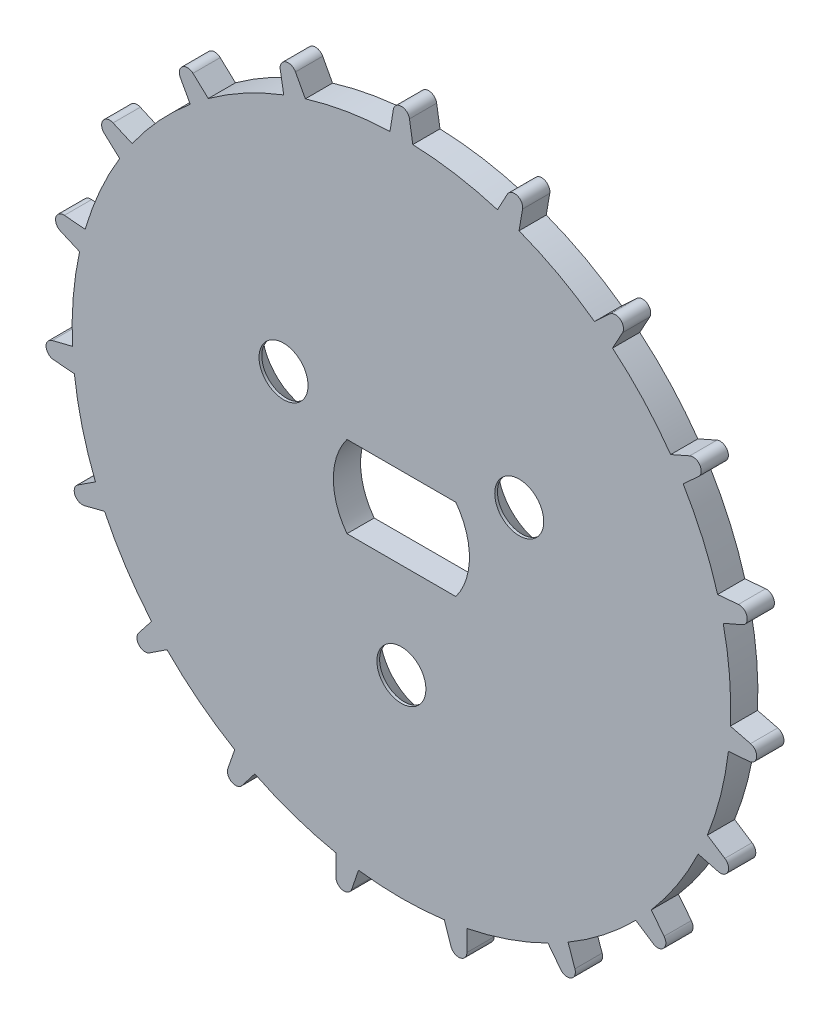
SolidWorks part; units mm, degrees
material "Нержавеющая сталь (ферритная)"
ref_plane "Спереди" through (0, 0, 0) normal (0, 0, 1) x (1, 0, 0)
ref_plane "Сверху" through (0, 0, 0) normal (0, 1, 0) x (1, 0, 0)
ref_plane "Справа" through (0, 0, 0) normal (1, 0, 0) x (0, 0, -1)
sketch "Эскиз7" plane through (0, 0, 0) normal (0, 0, 1) x (1, 0, 0)
  circle A0 centre (0, 0) radius 13.1 construction
  dimension "D1" = 26.2
sketch "Model" plane through (0, 0, 0) normal (0, 0, 1) x (1, 0, 0)
  circle A133 centre (0, 0) radius 12.1
  dimension "D1" = 24.2
extrude "База" add sketch "Model" against normal mid plane 1
sketch "Эскиз3" plane through (0, 0, 0.5) normal (0, 0, 1) x (1, 0, 0)
  line L0 (2, -1.5) -> (-2, -1.5)
  line L1 (-2, 1.5) -> (2, 1.5)
  arc A0 (-2, 1.5) -> (-2, -1.5) centre (0, 0) ccw
  arc A1 (2, -1.5) -> (2, 1.5) centre (0, 0) ccw
  point P5 (0, -1.5)
  point P6 (-2.5, 0)
  point P7 (2.5, 0)
  point P8 (0, 1.5)
  dimension "D2" = 2.5
  dimension "D1" = 4
extrude "Вырез-Вытянуть1" cut sketch "Эскиз3" along direction (0, 0, 1) on the side against the normal through all
sketch "Эскиз4" plane through (0, 0, 0.5) normal (0, 0, 1) x (1, 0, 0)
  line L0 (-0.5, 11.6) -> (0.5, 11.6)
  line L1 (-0.5, 11.6) -> (-0.2961, 12.8484)
  line L2 (0.2961, 12.8484) -> (0.5, 11.6)
  arc A5 (-0.2961, 12.8484) -> (0.2961, 12.8484) centre (0, 12.8) cw
  circle A9 centre (0, 0) radius 13.1 construction
  point P9 (0, 14.6609)
  point P15 (0, 11.6)
  dimension "D2" = 1.2
  dimension "D4" = 0.3
  dimension "D1" = 1
extrude "Зуб" add sketch "Эскиз4" against normal up to surface (1 mm away) up to face at (0, 0, -0.5)
pattern_circular "Круговой массив" count 19 over 360 about axis through (0, 0, 0) along (0, 0, 1) of "Зуб"
hole_wizard "Крепление шестерни M1.6" positions "Эскиз5" profile "Эскиз6" countersink size "M1.6" standard "DIN" end condition through all
sketch "Эскиз5" plane through (0, 0, -0.5) normal (0, 0, 1) x (1, 0, 0)
  circle A0 centre (0, 0) radius 5 construction
  point P0 (4.3301, 2.5)
  point P2 (0, -5)
  point P4 (-4.3301, 2.5)
  dimension "D1" = 10
  dimension "D2" = 120
  dimension "D3" = 120
sketch "Эскиз6" plane through (4.3301, 2.5, -0.5) normal (1, 0, 0) x (0, 1, 0)
  line L0 (0, 0) -> (0, 1)
  line L1 (0, 1) -> (0.9, 1)
  line L2 (0.9, 1) -> (0.9, 0.9)
  line L3 (0.9, 0.9) -> (1.8, 0)
  line L5 (1.8, 0) -> (0, 0)
  line L6 (-0.9, 0.9) -> (-1.8, 0) construction
  line L11 (0, -6.35) -> (0, 107.95) construction
  dimension "Диаметр сквозного отверстия" = 1.8
  dimension "Глубина сквозного отверстия" = 1
  dimension "Диаметр передней зенковки" = 3.6
  dimension "Угол передней зенковки" = 90
